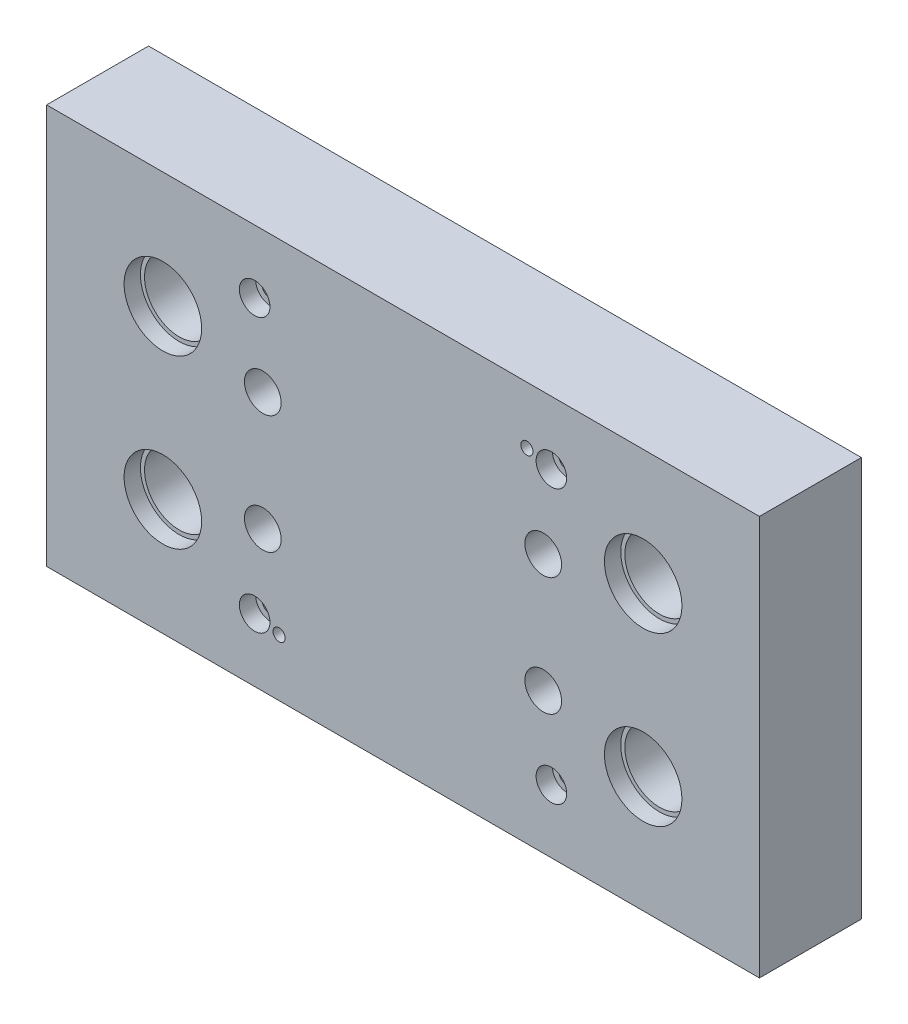
SolidWorks part; units mm, degrees
ref_plane "FP" through (0, 0, 0) normal (0, 0, 1) x (1, 0, 0)
ref_plane "TP" through (0, 0, 0) normal (0, 1, 0) x (1, 0, 0)
ref_plane "RP" through (0, 0, 0) normal (1, 0, 0) x (0, 0, -1)
sketch "Sketch1" plane through (0, 0, 0) normal (0, 0, 1) x (1, 0, 0)
  line L1 (-140, -98) -> (209.5, -98)
  line L2 (-140, -98) -> (-140, 98)
  line L3 (-140, 98) -> (209.5, 98)
  line L4 (209.5, -98) -> (209.5, 98)
extrude "Boss-Extrude1" add sketch "Sketch1" along normal blind 50
hole_wizard "CBORE for M8 SHCS1" positions "Sketch2" profile "Sketch3" counterbore size "M8" standard "ANSI Metric" end condition through all
sketch "Sketch2" plane through (0, 0, 50) normal (0, 0, 1) x (0.9063, -0.4226, 0)
  point P0 (125.7435, -15.2912)
  point P1 (69.1127, 106.1541)
  point P2 (-62.7551, 44.6631)
  point P3 (-6.1243, -76.7821)
sketch "Sketch3" plane through (107.5, -67, 50) normal (1, 0, 0) x (0, -1, 0)
  line L0 (0, 0) -> (0, 50)
  line L1 (0, 50) -> (4.5, 50)
  line L2 (4.5, 50) -> (4.5, 8)
  line L3 (4.5, 8) -> (7.5, 8)
  line L4 (7.5, 8) -> (7.5, 0)
  line L5 (7.5, 0) -> (0, 0)
  line L6 (0, -6.35) -> (0, 107.95) construction
  dimension "Thru Hole Dia." = 9
  dimension "Thru Hole Depth" = 50
  dimension "C'Bore Dia." = 15
  dimension "C'Bore Depth" = 8
hole_wizard "Ø6.0mm Clearance Dowel Hole1" positions "Sketch4" profile "Sketch5" hole size "Ø6.0" standard "ANSI Metric" end condition through all
sketch "Sketch4" plane through (0, 0, 50) normal (0, 0, 1) x (0.9063, -0.4226, 0)
  point P0 (56.9691, 103.8016)
  point P1 (6.0193, -74.4296)
sketch "Sketch5" plane through (95.5, 70, 50) normal (1, 0, 0) x (0, -1, 0)
  line L0 (0, 0) -> (0, 50)
  line L1 (0, 50) -> (3, 50)
  line L2 (3, 50) -> (3, 0)
  line L5 (3, 0) -> (0, 0)
  line L11 (0, -6.35) -> (0, 107.95) construction
  dimension "Thru Hole Dia." = 6
  dimension "Thru Hole Depth" = 50
hole_wizard "CBORE for M10 SHSS1" positions "Sketch7" profile "Sketch8" counterbore size "M10" standard "ANSI Metric" end condition through all
sketch "Sketch7" plane through (0, 0, 50) normal (0, 0, 1) x (0.9063, -0.4226, 0)
  point P0 (-43.0704, 11.9139)
  point P1 (-18.5585, -40.6519)
  point P2 (81.5469, 70.0239)
  point P3 (81.5469, 70.0239)
  point P4 (106.0588, 17.4581)
sketch "Sketch8" plane through (-34, 29, 50) normal (1, 0, 0) x (0, -1, 0)
  line L0 (0, 0) -> (0, 50)
  line L1 (0, 50) -> (5.5, 50)
  line L3 (5.5, 50) -> (5.5, 14.5)
  line L4 (5.5, 14.5) -> (9, 14.5)
  line L5 (9, 14.5) -> (9, 0)
  line L7 (9, 0) -> (0, 0)
  line L11 (0, -6.35) -> (0, 107.95) construction
  dimension "Thru Hole Dia." = 11
  dimension "Thru Hole Depth" = 50
  dimension "C'Bore Dia." = 18
  dimension "C'Bore Depth" = 14.5
hole_wizard "Hole1" positions "3DSketch1" profile "Sketch9" legacy
sketch3d "3DSketch1"
  line L0 (209.5, -98, 50) -> (209.5, 98, 50) construction
  line L1 (209.5, 98, 50) -> (-140, 98, 50) construction
  line L2 (-140, -98, 50) -> (209.5, -98, 50) construction
  line L3 (-140, 98, 50) -> (-140, -98, 50) construction
  point P0 (-83, 41, 50)
  point P2 (-83, -41, 50)
  point P4 (152.5, 41, 50)
  point P6 (152.5, -41, 50)
  dimension "D1" = 57
  dimension "D2" = 57
  dimension "D3" = 57
  dimension "D4" = 57
  dimension "D5" = 57
  dimension "D6" = 57
  dimension "D7" = 57
  dimension "D8" = 57
sketch "Sketch9" plane through (-83, 41, 50) normal (1, 0, 0) x (0, -1, 0)
  line L0 (0, 0) -> (0, 50)
  line L1 (0, 50) -> (17, 50)
  line L2 (17, 50) -> (17, 8)
  line L3 (17, 8) -> (19, 8)
  line L4 (19, 8) -> (19, 0)
  line L5 (19, 0) -> (0, 0)
  line L6 (0, 110) -> (0, -10) construction
  dimension "Diameter" = 34
  dimension "Depth" = 50
  dimension "C-Bore Diameter" = 38
  dimension "C-Bore Depth" = 8
